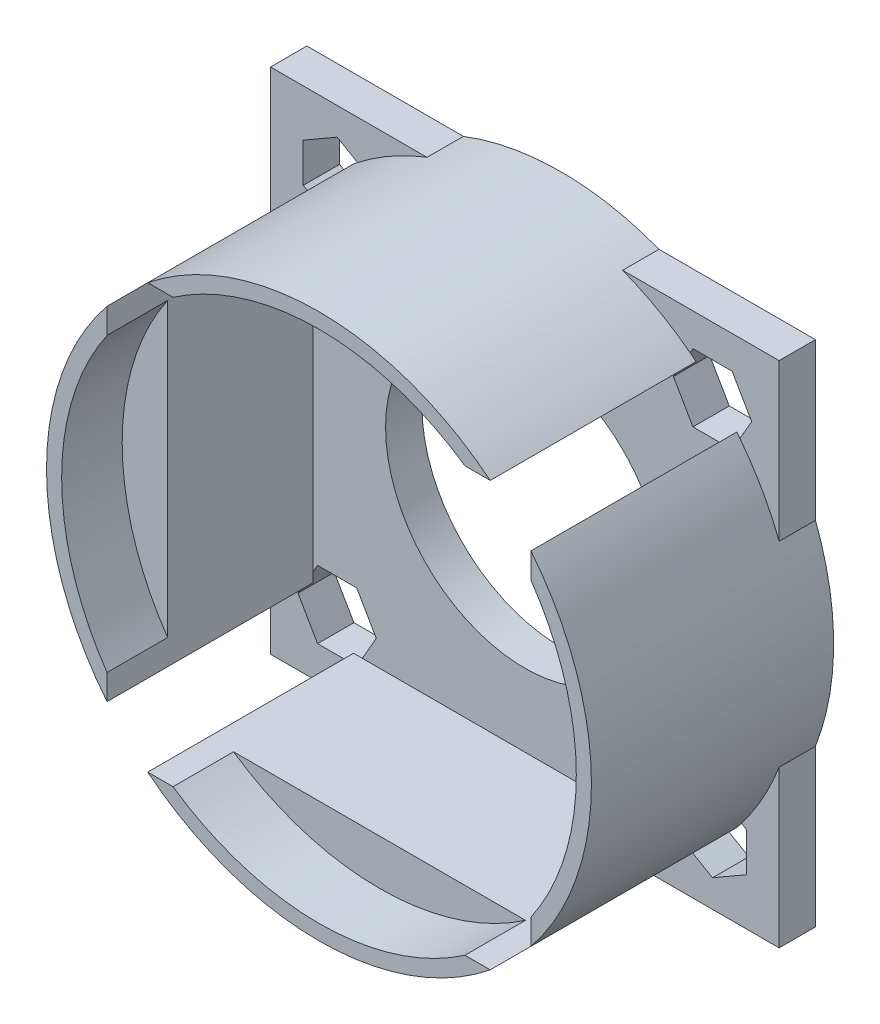
SolidWorks part; units mm, degrees
ref_plane "前视基准面" through (0, 0, 0) normal (0, 0, 1) x (1, 0, 0)
ref_plane "上视基准面" through (0, 0, 0) normal (0, 1, 0) x (1, 0, 0)
ref_plane "右视基准面" through (0, 0, 0) normal (1, 0, 0) x (0, 0, -1)
sketch "草图1" plane through (0, 0, 0) normal (0, 0, 1) x (1, 0, 0)
  line L1 (21, -21) -> (-21, -21)
  line L2 (21, -21) -> (21, 21)
  line L3 (21, 21) -> (-21, 21)
  line L4 (-21, -21) -> (-21, 21)
  line L5 (0, 21) -> (0, -21) construction
  line L6 (21, 0) -> (-21, 0) construction
  line L7 (15.5, -15.5) -> (-15.5, -15.5) construction
  line L8 (15.5, -15.5) -> (15.5, 15.5) construction
  line L9 (15.5, 15.5) -> (-15.5, 15.5) construction
  line L10 (-15.5, -15.5) -> (-15.5, 15.5) construction
  line L11 (0, 15.5) -> (0, -15.5) construction
  line L12 (15.5, 0) -> (-15.5, 0) construction
  circle A0 centre (15.5, 15.5) radius 1.5
  circle A1 centre (15.5, -15.5) radius 1.5
  circle A2 centre (-15.5, -15.5) radius 1.5
  circle A3 centre (-15.5, 15.5) radius 1.5
  circle A4 centre (0, 0) radius 11.5
  point P0 (0, 0)
  point P4 (0, 0)
  point P24 (0, 0)
  dimension "D5" = 3
  dimension "D7" = 23
  dimension "D1" = 42
  dimension "D2" = 42
  dimension "D3" = 31
  dimension "D4" = 31
  dimension "D6" = 4
extrude "凸台-拉伸1" add sketch "草图1" along normal blind 3
sketch "草图2" plane through (0, 0, 0) normal (0, 0, -1) x (-1, 0, 0)
  line L1 (17.5, -14.1421) -> (-17.5, -14.1421)
  line L2 (17.5, -14.1421) -> (17.5, 14.1421)
  line L3 (17.5, 14.1421) -> (-17.5, 14.1421)
  line L4 (-17.5, -14.1421) -> (-17.5, 14.1421)
  line L5 (0, 14.1421) -> (0, -14.1421) construction
  line L6 (17.5, 0) -> (-17.5, 0) construction
  line L7 (14.1421, -17.5) -> (-14.1421, -17.5)
  line L8 (14.1421, -17.5) -> (14.1421, 17.5)
  line L9 (14.1421, 17.5) -> (-14.1421, 17.5)
  line L10 (-14.1421, -17.5) -> (-14.1421, 17.5)
  line L11 (0, 17.5) -> (0, -17.5) construction
  line L12 (14.1421, 0) -> (-14.1421, 0) construction
  circle A0 centre (0, 0) radius 22.5
  circle A1 centre (0, 0) radius 17.5
  line M3 (21, -21) -> (21, 21)
  line M4 (21, 21) -> (-21, 21)
  line M5 (-21, 21) -> (-21, -21)
  line M6 (-21, -21) -> (21, -21)
  dimension "D1" = 45
  dimension "D2" = 35
extrude "凸台-拉伸2" add sketch "草图2" against normal blind 20 contours L9 A0 | L4 A0 | L2 A0 | L7 A0 | A0 M5 | A0 M3 | A0 M4 | A0 M6
sketch "草图5" plane through (0, 0, 20) normal (0, 0, 1) x (1, 0, 0)
  circle A0 centre (0, 0) radius 21.25
  dimension "D1" = 42.5
extrude "切除-拉伸3" cut sketch "草图5" against normal blind 5
sketch "草图6" plane through (0, 0, 0) normal (0, 0, -1) x (-1, 0, 0)
  line L1 (18.3, 17.1166) -> (15.5, 18.7332)
  line L2 (15.5, 18.7332) -> (12.7, 17.1166)
  line L3 (12.7, 17.1166) -> (12.7, 13.8834)
  line L4 (12.7, 13.8834) -> (15.5, 12.2668)
  line L5 (15.5, 12.2668) -> (18.3, 13.8834)
  line L6 (18.3, 13.8834) -> (18.3, 17.1166)
  circle A0 centre (15.5, 15.5) radius 2.8 construction
  dimension "D1" = 5.6
extrude "切除-拉伸4" cut sketch "草图6" against normal up to surface (3 mm away) up to face at (0, 0, 3)
pattern_circular "阵列(圆周)1" count 4 over 360 about axis through (0, 0, 0) along (0, 0, 1) of "切除-拉伸4"
